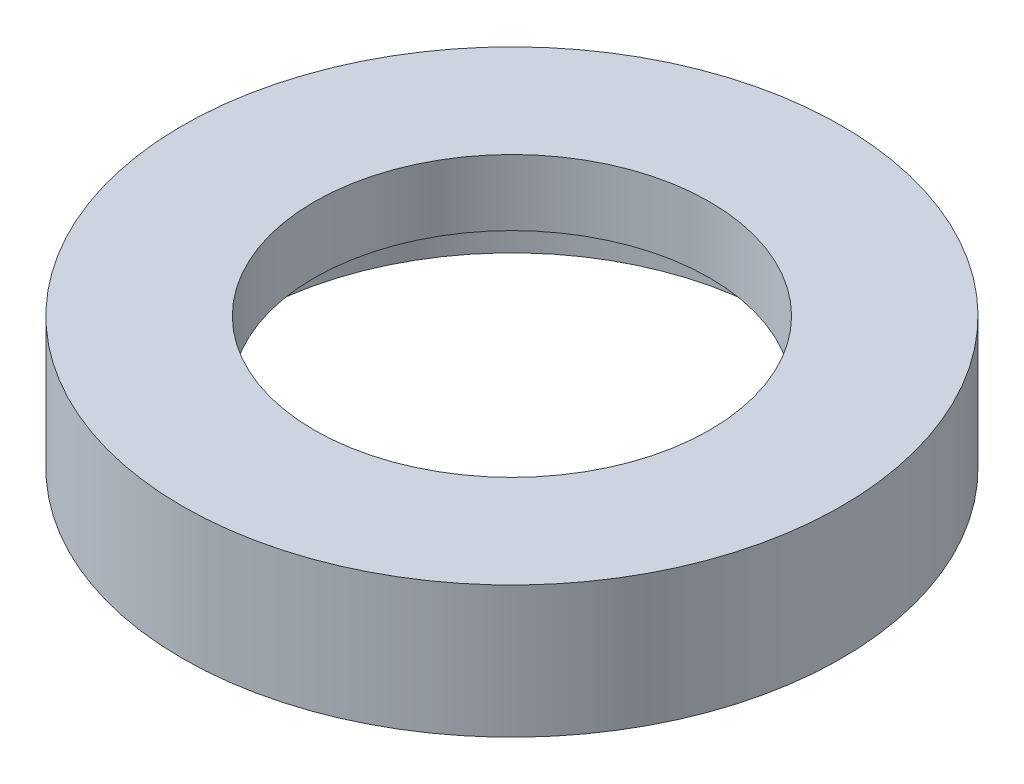
SolidWorks part; units mm, degrees
ref_plane "Front Plane" through (0, 0, 0) normal (0, 0, 1) x (1, 0, 0)
ref_plane "Top Plane" through (0, 0, 0) normal (0, 1, 0) x (1, 0, 0)
ref_plane "Right Plane" through (0, 0, 0) normal (1, 0, 0) x (0, 0, -1)
sketch "Sketch1" plane through (0, 0, 0) normal (0, 1, 0) x (1, 0, 0)
  circle A0 centre (0, 0) radius 4
  circle A1 centre (0, 0) radius 5
  dimension "D1" = 10
  dimension "D2" = 8
extrude "Boss-Extrude1" add sketch "Sketch1" along normal blind 2
sketch "Sketch2" plane through (0, 2, 0) normal (0, 1, 0) x (1, 0, 0)
  circle A0 centre (0, 0) radius 4
  circle A1 centre (0, 0) radius 3
  dimension "D1" = 6
extrude "Boss-Extrude2" add sketch "Sketch2" against normal blind 1.9
sketch "Sketch3" plane through (0, 0.1, 0) normal (0, -1, 0) x (1, 0, 0)
  circle A1 centre (0, 0) radius 4
extrude "Boss-Extrude4" add sketch "Sketch3" along normal blind 0.1
sketch "Sketch4" plane through (0, 0, 0) normal (0, -1, 0) x (1, 0, 0)
  circle A0 centre (0, 0) radius 4
  dimension "D1" = 8
extrude "Cut-Extrude1" cut sketch "Sketch4" against normal blind 1
